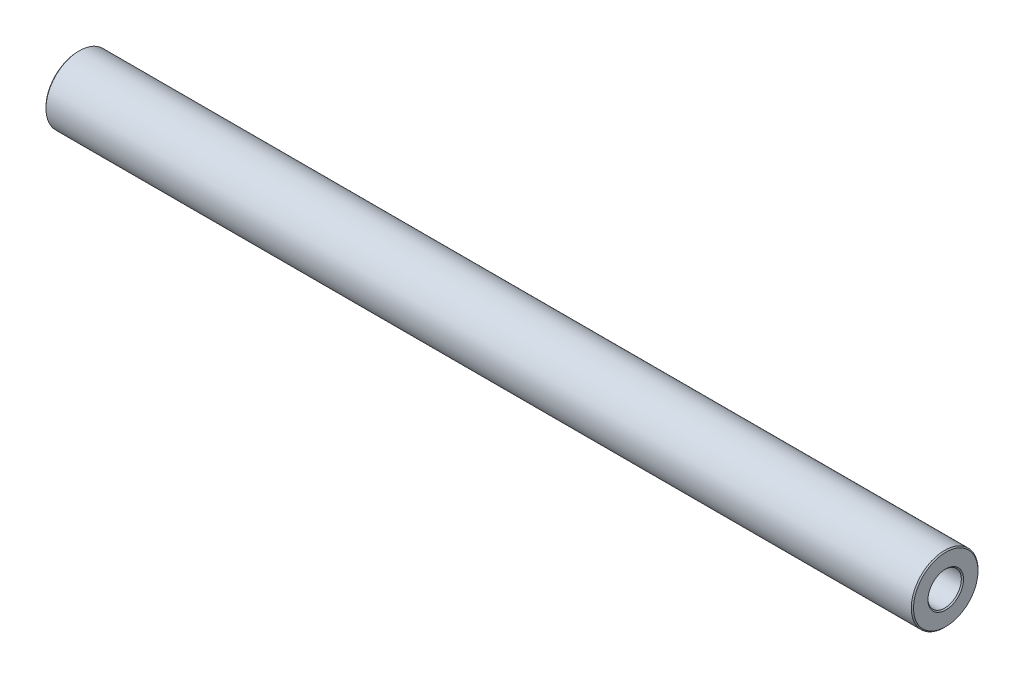
SolidWorks part; units mm, degrees
ref_plane "Front Plane" through (0, 0, 0) normal (0, 0, 1) x (1, 0, 0)
ref_plane "Top Plane" through (0, 0, 0) normal (0, 1, 0) x (1, 0, 0)
ref_plane "Right Plane" through (0, 0, 0) normal (1, 0, 0) x (0, 0, -1)
sketch "Sketch1" plane through (0, 0, 0) normal (1, 0, 0) x (0, 0, -1)
  circle A0 centre (0, 0) radius 3
  dimension "D1" = 6
extrude "Boss-Extrude1" add sketch "Sketch1" along normal mid plane 78
sketch "Sketch2" plane through (-39, 0, 0) normal (-1, 0, 0) x (0, 0, 1)
  circle A0 centre (0, 0) radius 1.5
  dimension "D1" = 3
extrude "Cut-Extrude1" cut sketch "Sketch2" against normal blind 7
sketch "Sketch3" plane through (39, 0, 0) normal (1, 0, 0) x (0, 0, -1)
  circle A0 centre (0, 0) radius 1.5
  dimension "D1" = 3
extrude "Cut-Extrude2" cut sketch "Sketch3" against normal blind 7
chamfer "Chamfer1" distance 0.1 angle 45 4 edges at (-39, 0, 1.5) (-39, 0, -3) (39, 0, -1.5) (39, 0, -3)
